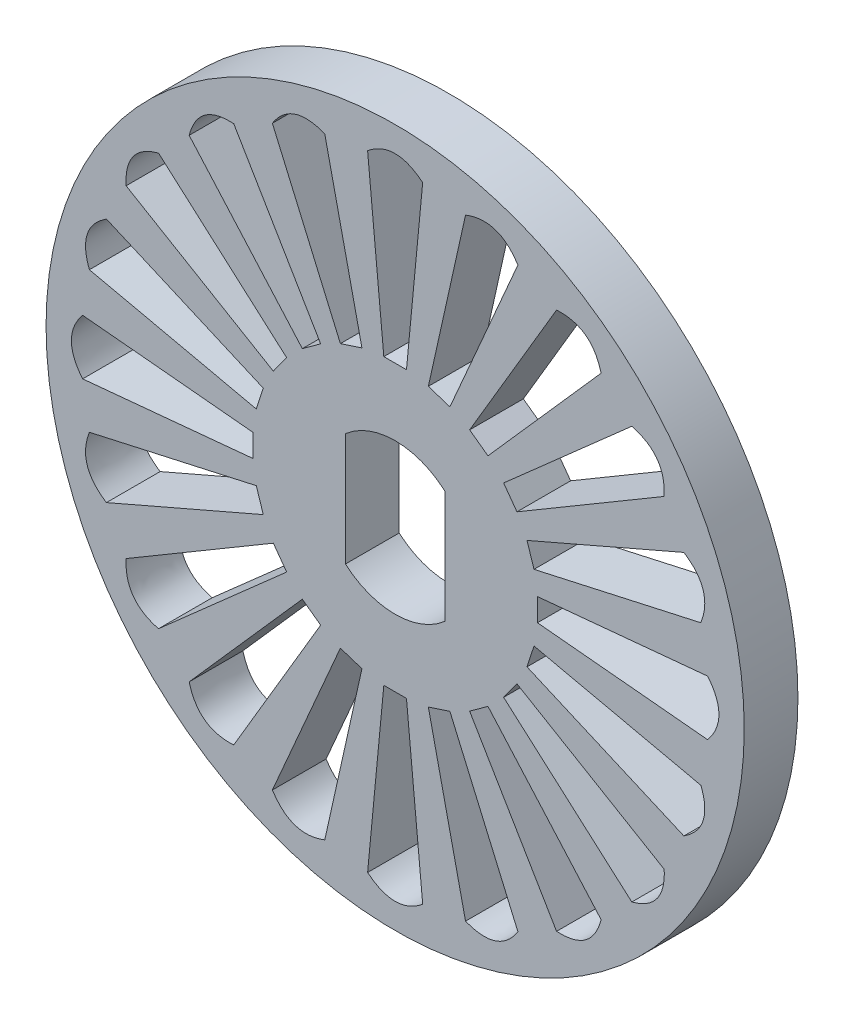
SolidWorks part; units mm, degrees
ref_plane "Front Plane" through (0, 0, 0) normal (0, 0, 1) x (1, 0, 0)
ref_plane "Top Plane" through (0, 0, 0) normal (0, 1, 0) x (1, 0, 0)
ref_plane "Right Plane" through (0, 0, 0) normal (1, 0, 0) x (0, 0, -1)
sketch "Sketch1" plane through (0, 0, 0) normal (0, 0, 1) x (1, 0, 0)
  line L0 (0, 29.3396) -> (0, -28.4316) construction
  line L1 (-34.5346, 0) -> (35.2675, 0) construction
  circle A0 centre (0, 0) radius 13
  dimension "D1" = 26
extrude "Boss-Extrude1" add sketch "Sketch1" along normal blind 2
sketch "Sketch2" plane through (0, 0, 2) normal (0, 0, 1) x (1, 0, 0)
  line L0 (0, 12.0457) -> (0, -12.3213) construction
  line L1 (-16.0712, 0) -> (16.7447, 0) construction
  line L2 (1.85, 2.1018) -> (1.85, -2.1018)
  line L3 (-1.85, 2.1018) -> (-1.85, -2.1018)
  arc A0 (-1.85, -2.1018) -> (1.85, -2.1018) centre (0, 0) ccw
  arc A1 (1.85, 2.1018) -> (-1.85, 2.1018) centre (0, 0) ccw
  point P11 (0, 0)
  dimension "D1" = 3.7
  dimension "D2" = 5.6
extrude "Cut-Extrude1" cut sketch "Sketch2" against normal blind 2
sketch "Sketch3" plane through (0, 0, 2) normal (0, 0, 1) x (1, 0, 0)
  line L0 (0, 13.934) -> (0, -12.3825) construction
  line L1 (-14.8773, 0) -> (14.2345, 0) construction
  line L2 (-0.4219, 5.3) -> (0.4219, 5.3)
  line L3 (0.4219, 5.3) -> (1.0258, 11.6382)
  line L4 (-0.4219, 5.3) -> (-1.0258, 11.6382)
  line L6 (2.039, 4.9102) -> (4.572, 10.7516)
  line L7 (1.2365, 5.171) -> (2.039, 4.9102)
  line L8 (1.2365, 5.171) -> (2.6209, 11.3856)
  line L9 (3.4566, 4.0398) -> (7.6706, 8.8126)
  line L10 (2.7739, 4.5358) -> (3.4566, 4.0398)
  line L11 (2.7739, 4.5358) -> (6.0109, 10.0184)
  line L12 (4.5358, 2.7739) -> (10.0184, 6.0109)
  line L13 (4.0398, 3.4566) -> (4.5358, 2.7739)
  line L14 (4.0398, 3.4566) -> (8.8126, 7.6706)
  line L15 (5.171, 1.2365) -> (11.3856, 2.6209)
  line L16 (4.9102, 2.039) -> (5.171, 1.2365)
  line L17 (4.9102, 2.039) -> (10.7516, 4.572)
  line L18 (5.3, -0.4219) -> (11.6382, -1.0258)
  line L19 (5.3, 0.4219) -> (5.3, -0.4219)
  line L20 (5.3, 0.4219) -> (11.6382, 1.0258)
  line L21 (4.9102, -2.039) -> (10.7516, -4.572)
  line L22 (5.171, -1.2365) -> (4.9102, -2.039)
  line L23 (5.171, -1.2365) -> (11.3856, -2.6209)
  line L24 (4.0398, -3.4566) -> (8.8126, -7.6706)
  line L25 (4.5358, -2.7739) -> (4.0398, -3.4566)
  line L26 (4.5358, -2.7739) -> (10.0184, -6.0109)
  line L27 (2.7739, -4.5358) -> (6.0109, -10.0184)
  line L28 (3.4566, -4.0398) -> (2.7739, -4.5358)
  line L29 (3.4566, -4.0398) -> (7.6706, -8.8126)
  line L30 (1.2365, -5.171) -> (2.6209, -11.3856)
  line L31 (2.039, -4.9102) -> (1.2365, -5.171)
  line L32 (2.039, -4.9102) -> (4.572, -10.7516)
  line L33 (-0.4219, -5.3) -> (-1.0258, -11.6382)
  line L34 (0.4219, -5.3) -> (-0.4219, -5.3)
  line L35 (0.4219, -5.3) -> (1.0258, -11.6382)
  line L36 (-2.039, -4.9102) -> (-4.572, -10.7516)
  line L37 (-1.2365, -5.171) -> (-2.039, -4.9102)
  line L38 (-1.2365, -5.171) -> (-2.6209, -11.3856)
  line L39 (-3.4566, -4.0398) -> (-7.6706, -8.8126)
  line L40 (-2.7739, -4.5358) -> (-3.4566, -4.0398)
  line L41 (-2.7739, -4.5358) -> (-6.0109, -10.0184)
  line L42 (-4.5358, -2.7739) -> (-10.0184, -6.0109)
  line L43 (-4.0398, -3.4566) -> (-4.5358, -2.7739)
  line L44 (-4.0398, -3.4566) -> (-8.8126, -7.6706)
  line L45 (-5.171, -1.2365) -> (-11.3856, -2.6209)
  line L46 (-4.9102, -2.039) -> (-5.171, -1.2365)
  line L47 (-4.9102, -2.039) -> (-10.7516, -4.572)
  line L48 (-5.3, 0.4219) -> (-11.6382, 1.0258)
  line L49 (-5.3, -0.4219) -> (-5.3, 0.4219)
  line L50 (-5.3, -0.4219) -> (-11.6382, -1.0258)
  line L51 (-4.9102, 2.039) -> (-10.7516, 4.572)
  line L52 (-5.171, 1.2365) -> (-4.9102, 2.039)
  line L53 (-5.171, 1.2365) -> (-11.3856, 2.6209)
  line L54 (-4.0398, 3.4566) -> (-8.8126, 7.6706)
  line L55 (-4.5358, 2.7739) -> (-4.0398, 3.4566)
  line L56 (-4.5358, 2.7739) -> (-10.0184, 6.0109)
  line L57 (-2.7739, 4.5358) -> (-6.0109, 10.0184)
  line L58 (-3.4566, 4.0398) -> (-2.7739, 4.5358)
  line L59 (-3.4566, 4.0398) -> (-7.6706, 8.8126)
  line L60 (-1.2365, 5.171) -> (-2.6209, 11.3856)
  line L61 (-2.039, 4.9102) -> (-1.2365, 5.171)
  line L62 (-2.039, 4.9102) -> (-4.572, 10.7516)
  arc A2 (1.85, 2.1018) -> (-1.85, 2.1018) centre (0, 0) ccw construction
  spline S0 degree 2 poles (-1.0258, 11.6382) (0, 12.4761) (1.0258, 11.6382) knots 0 0 0 1 1 1
  spline S1 degree 2 poles (2.6209, 11.3856) (3.8553, 11.8655) (4.572, 10.7516) knots 0 0 0 1 1 1
  spline S2 degree 2 poles (6.0109, 10.0184) (7.3333, 10.0934) (7.6706, 8.8126) knots 0 0 0 1 1 1
  spline S3 degree 2 poles (8.8126, 7.6706) (10.0934, 7.3333) (10.0184, 6.0109) knots 0 0 0 1 1 1
  spline S4 degree 2 poles (10.7516, 4.572) (11.8655, 3.8553) (11.3856, 2.6209) knots 0 0 0 1 1 1
  spline S5 degree 2 poles (11.6382, 1.0258) (12.4761, 0) (11.6382, -1.0258) knots 0 0 0 1 1 1
  spline S6 degree 2 poles (11.3856, -2.6209) (11.8655, -3.8553) (10.7516, -4.572) knots 0 0 0 1 1 1
  spline S7 degree 2 poles (10.0184, -6.0109) (10.0934, -7.3333) (8.8126, -7.6706) knots 0 0 0 1 1 1
  spline S8 degree 2 poles (7.6706, -8.8126) (7.3333, -10.0934) (6.0109, -10.0184) knots 0 0 0 1 1 1
  spline S9 degree 2 poles (4.572, -10.7516) (3.8553, -11.8655) (2.6209, -11.3856) knots 0 0 0 1 1 1
  spline S10 degree 2 poles (1.0258, -11.6382) (0, -12.4761) (-1.0258, -11.6382) knots 0 0 0 1 1 1
  spline S11 degree 2 poles (-2.6209, -11.3856) (-3.8553, -11.8655) (-4.572, -10.7516) knots 0 0 0 1 1 1
  spline S12 degree 2 poles (-6.0109, -10.0184) (-7.3333, -10.0934) (-7.6706, -8.8126) knots 0 0 0 1 1 1
  spline S13 degree 2 poles (-8.8126, -7.6706) (-10.0934, -7.3333) (-10.0184, -6.0109) knots 0 0 0 1 1 1
  spline S14 degree 2 poles (-10.7516, -4.572) (-11.8655, -3.8553) (-11.3856, -2.6209) knots 0 0 0 1 1 1
  spline S15 degree 2 poles (-11.6382, -1.0258) (-12.4761, 0) (-11.6382, 1.0258) knots 0 0 0 1 1 1
  spline S16 degree 2 poles (-11.3856, 2.6209) (-11.8655, 3.8553) (-10.7516, 4.572) knots 0 0 0 1 1 1
  spline S17 degree 2 poles (-10.0184, 6.0109) (-10.0934, 7.3333) (-8.8126, 7.6706) knots 0 0 0 1 1 1
  spline S18 degree 2 poles (-7.6706, 8.8126) (-7.3333, 10.0934) (-6.0109, 10.0184) knots 0 0 0 1 1 1
  spline S19 degree 2 poles (-4.572, 10.7516) (-3.8553, 11.8655) (-2.6209, 11.3856) knots 0 0 0 1 1 1
  point P10 (0.3686, 6.8)
  point P18 (1.3734, 11.6658)
  point P19 (-0.3262, 4.8)
  point P23 (-0.6409, 5.2386)
  point P30 (1.0258, 11.6382)
  point P91 (0, 0)
  point P121 (0, 0)
  point P122 (0, 0)
  point P137 (0, 0)
  point P152 (0, 0)
  point P180 (0, 0)
  point P181 (0, 0)
  dimension "D2" = 2.5
  dimension "D1" = 20
extrude "Cut-Extrude2" cut sketch "Sketch3" against normal blind 2
